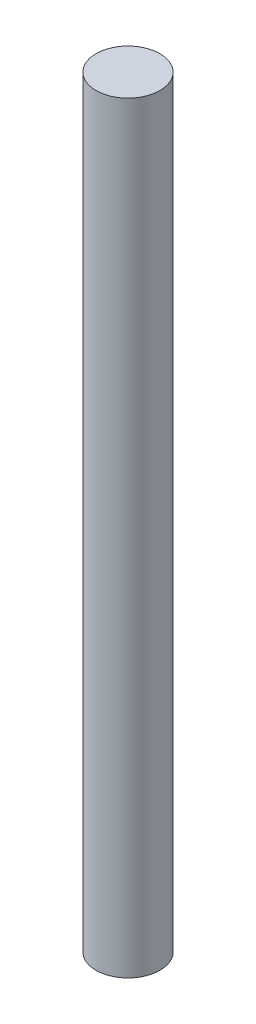
SolidWorks part; units mm, degrees
material "AISI 1020"
ref_plane "Alzado" through (0, 0, 0) normal (0, 0, 1) x (1, 0, 0)
ref_plane "Planta" through (0, 0, 0) normal (0, 1, 0) x (1, 0, 0)
ref_plane "Vista lateral" through (0, 0, 0) normal (1, 0, 0) x (0, 0, -1)
sketch "Croquis1" plane through (0, 0, 0) normal (0, 1, 0) x (1, 0, 0)
  circle A0 centre (0, 0) radius 5
  dimension "D1" = 10
extrude "Saliente-Extruir1" add sketch "Croquis1" along normal blind 40.3
sketch "Croquis2" plane through (0, 40.3, 0) normal (0, 1, 0) x (1, 0, 0)
  circle A0 centre (0, 0) radius 5
  dimension "D1" = 10
extrude "Saliente-Extruir2" add sketch "Croquis2" along normal blind 79
